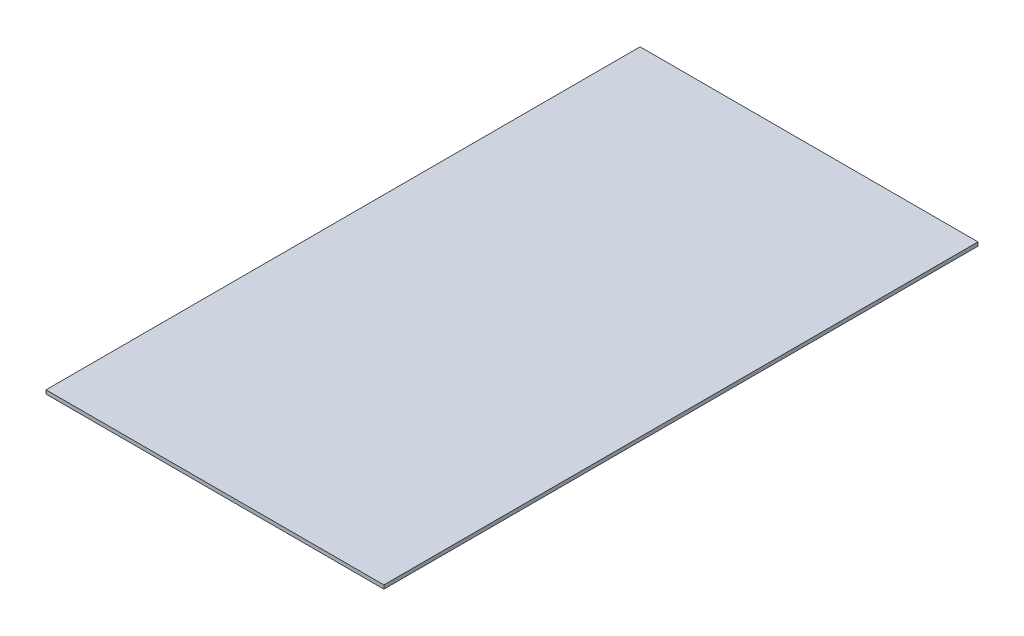
SolidWorks part; units mm, degrees
ref_plane "Front Plane" through (0, 0, 0) normal (0, 0, 1) x (1, 0, 0)
ref_plane "Top Plane" through (0, 0, 0) normal (0, 1, 0) x (1, 0, 0)
ref_plane "Right Plane" through (0, 0, 0) normal (1, 0, 0) x (0, 0, -1)
sketch "Sketch1" plane through (0, 0, 0) normal (0, 1, 0) x (1, 0, 0)
  line L1 (-227.5, 400) -> (227.5, 400)
  line L2 (-227.5, 400) -> (-227.5, -400)
  line L3 (-227.5, -400) -> (227.5, -400)
  line L4 (227.5, 400) -> (227.5, -400)
  line L5 (-227.5, 400) -> (227.5, -400) construction
  line L6 (-227.5, -400) -> (227.5, 400) construction
  point P0 (0, 0)
  dimension "D1" = 800
  dimension "D2" = 455
extrude "Boss-Extrude1" add sketch "Sketch1" along normal blind 5 contours L2 L3 L4 L1
